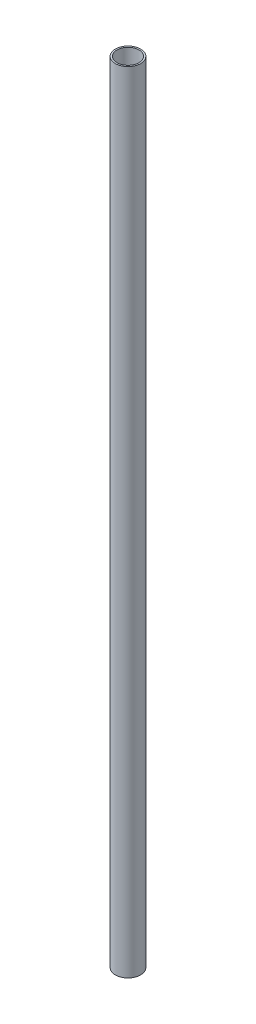
SolidWorks part; units mm, degrees
material "Thornel Mat VMA"
ref_plane "Front Plane" through (0, 0, 0) normal (0, 0, 1) x (1, 0, 0)
ref_plane "Top Plane" through (0, 0, 0) normal (0, 1, 0) x (1, 0, 0)
ref_plane "Right Plane" through (0, 0, 0) normal (1, 0, 0) x (0, 0, -1)
sketch "Sketch1" plane through (0, 0, 0) normal (0, 1, 0) x (1, 0, 0)
  circle A0 centre (0, 0) radius 8
  circle A1 centre (0, 0) radius 7
  dimension "D1" = 16
  dimension "D2" = 14
extrude "Boss-Extrude1" add sketch "Sketch1" along normal mid plane 500
